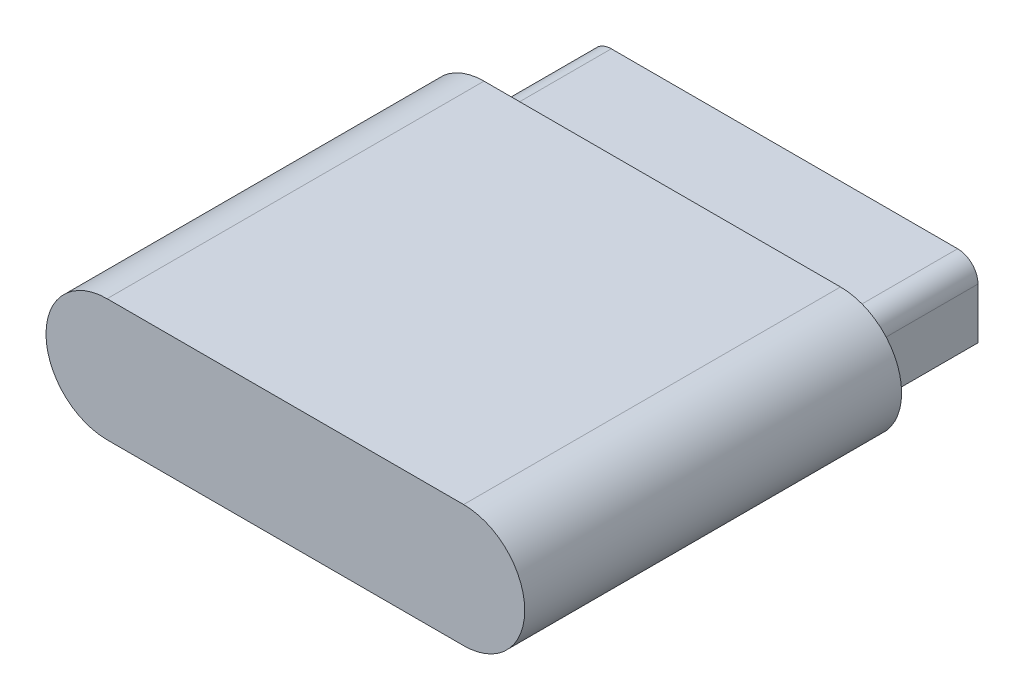
SolidWorks part; units mm, degrees
ref_plane "Front Plane" through (0, 0, 0) normal (0, 0, 1) x (1, 0, 0)
ref_plane "Top Plane" through (0, 0, 0) normal (0, 1, 0) x (1, 0, 0)
ref_plane "Right Plane" through (0, 0, 0) normal (1, 0, 0) x (0, 0, -1)
sketch "Sketch1" plane through (0, 0, 0) normal (0, 0, 1) x (1, 0, 0)
  line L1 (6, 0) -> (41, 0)
  line L3 (6, 12) -> (41, 12)
  arc A0 (6, 12) -> (6, 0) centre (6, 6) ccw
  arc A1 (41, 0) -> (41, 12) centre (41, 6) ccw
  dimension "D3" = 12
  dimension "D4" = 6
  dimension "D1" = 6
  dimension "D2" = 12
  dimension "D5" = 35
extrude "Boss-Extrude2" add sketch "Sketch1" against normal blind 37
sketch "Sketch2" plane through (0, 0, -37) normal (0, 0, -1) x (-1, 0, 0)
  line L0 (-42.5, 2) -> (-4.5, 2)
  line L1 (-4.5, 2) -> (-4.5, 7)
  line L2 (-6.5, 9) -> (-40.5, 9)
  line L3 (-42.5, 7) -> (-42.5, 2)
  line L4 (-41, 12) -> (-6, 12) construction
  line L5 (-23.5, 12) -> (-23.5, 0) construction
  line L6 (-6, 0) -> (-41, 0) construction
  line L7 (-23.5, 9) -> (-23.5, 2) construction
  arc A0 (-4.5, 7) -> (-6.5, 9) centre (-6.5, 7) ccw
  arc A1 (-40.5, 9) -> (-42.5, 7) centre (-40.5, 7) ccw
  dimension "D1" = 2
  dimension "D2" = 38
  dimension "D3" = 7
  dimension "D4" = 10
extrude "Boss-Extrude3" add sketch "Sketch2" along normal blind 12
